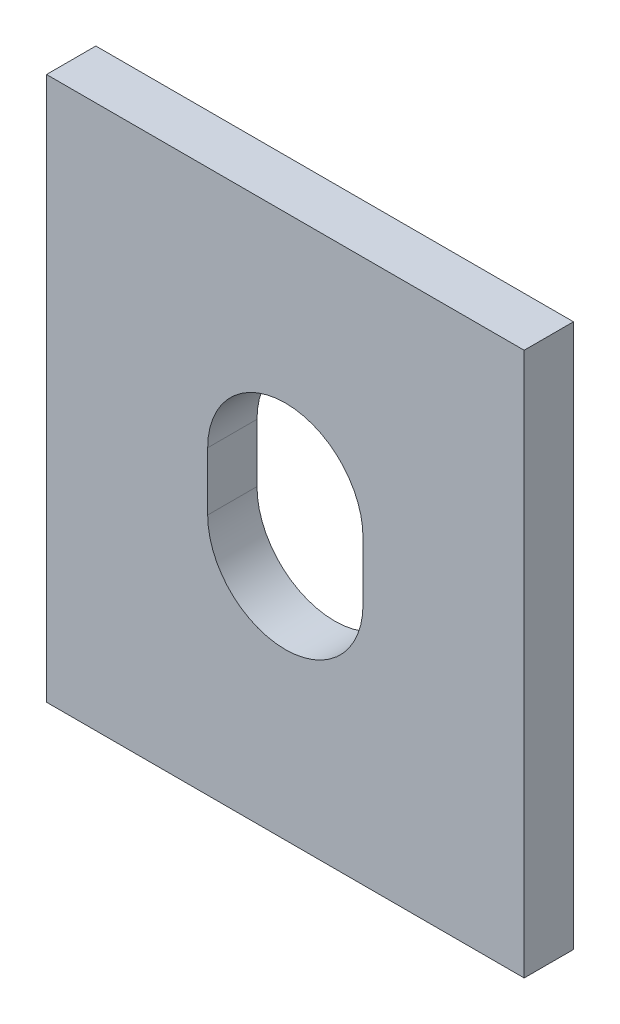
SolidWorks part; units mm, degrees
material "Low Carbon Steel"
ref_plane "Front Plane" through (0, 0, 0) normal (0, 0, 1) x (1, 0, 0)
ref_plane "Top Plane" through (0, 0, 0) normal (0, 1, 0) x (1, 0, 0)
ref_plane "Right Plane" through (0, 0, 0) normal (1, 0, 0) x (0, 0, -1)
sketch "Sketch1" plane through (0, 0, 0) normal (0, 0, 1) x (1, 0, 0)
  line L1 (-123, 140) -> (123, 140)
  line L2 (-123, 140) -> (-123, -140)
  line L3 (-123, -140) -> (123, -140)
  line L4 (123, 140) -> (123, -140)
  line L6 (123, -140) -> (-123, 140) construction
  dimension "D1" = 280
  dimension "D2" = 246
extrude "Boss-Extrude1" add sketch "Sketch1" along normal blind 25.4
sketch "Sketch2" plane through (0, 0, 25.4) normal (0, 0, 1) x (1, 0, 0)
  line L0 (0, 15) -> (0, -15) construction
  line L1 (40, 15) -> (40, -15)
  line L2 (-40, 15) -> (-40, -15)
  line L4 (123, 140) -> (-123, 140) construction
  arc A0 (40, 15) -> (-40, 15) centre (0, 15) ccw
  arc A1 (-40, -15) -> (40, -15) centre (0, -15) ccw
  point P3 (0, 0)
  dimension "D2" = 30
  dimension "D1" = 80
  dimension "D3" = 140
extrude "Cut-Extrude1" cut sketch "Sketch2" against normal through all
other "Freeze***"
